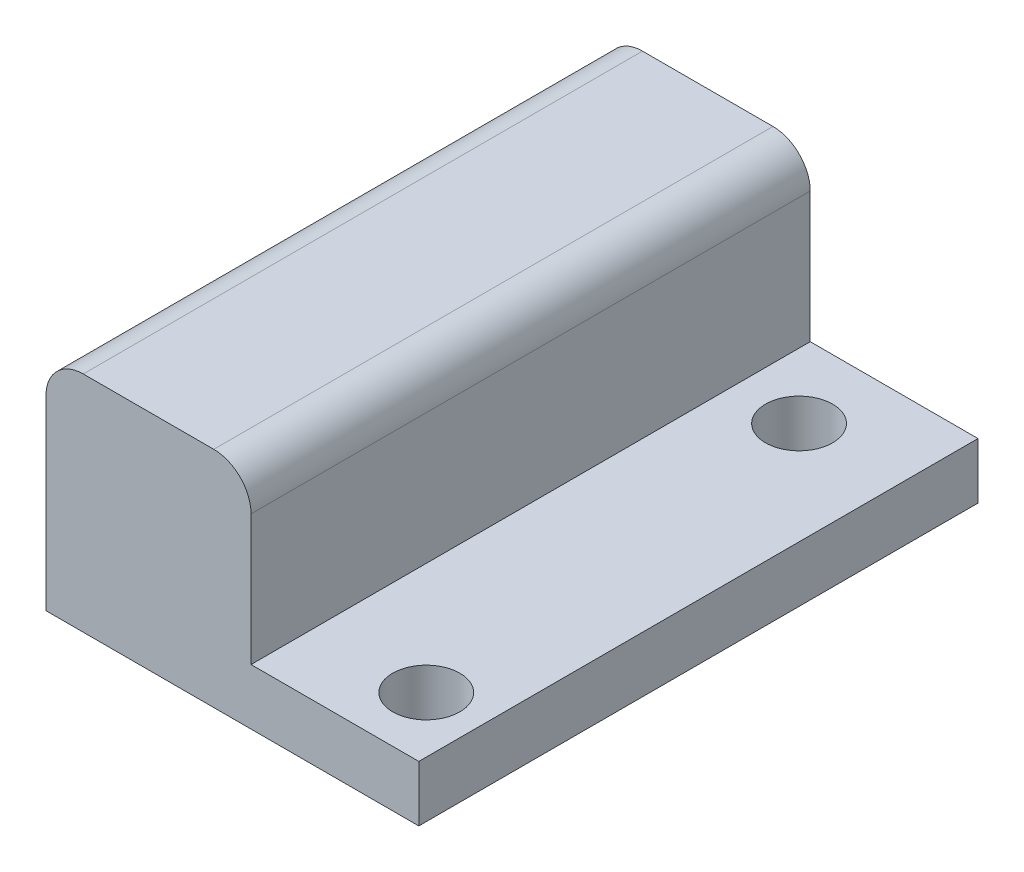
SolidWorks part; units mm, degrees
ref_plane "Front Plane" through (0, 0, 0) normal (0, 0, 1) x (1, 0, 0)
ref_plane "Top Plane" through (0, 0, 0) normal (0, 1, 0) x (1, 0, 0)
ref_plane "Right Plane" through (0, 0, 0) normal (1, 0, 0) x (0, 0, -1)
sketch "Sketch1" plane through (0, 0, 0) normal (0, 1, 0) x (1, 0, 0)
  line L1 (-19.812, 6.4835) -> (5.588, 6.4835)
  line L2 (-19.812, 6.4835) -> (-19.812, -31.6165)
  line L3 (-19.812, -31.6165) -> (5.588, -31.6165)
  line L4 (5.588, 6.4835) -> (5.588, -31.6165)
  circle A0 centre (-1.397, 1.2765) radius 2.286
  circle A1 centre (1.778, -27.2985) radius 2.286
  point P5 (0, 0)
  point P6 (-19.812, -12.5665)
  point P11 (0, 0)
  point P12 (0.508, -12.5665)
  point P13 (-1.9309, -28.9676)
  point P14 (1.7682, 1.088)
  point P15 (0, 0)
  point P16 (-2.1793, 1.2765)
  dimension "D1" = 28.575
  dimension "D2" = 4.572
  dimension "D3" = 3.81
  dimension "D4" = 3.175
  dimension "D5" = 38.1
  dimension "D6" = 25.4
  dimension "D7" = 4.318
extrude "Boss-Extrude1" add sketch "Sketch1" along normal blind 3.81
sketch "Sketch2" plane through (0, 3.81, 0) normal (0, 1, 0) x (1, 0, 0)
  line L0 (-19.812, 6.4835) -> (-19.812, -31.6165)
  line L1 (-19.812, -31.6165) -> (-5.842, -31.6165)
  line L2 (-19.812, -31.6165) -> (5.588, -31.6165) construction
  line L3 (-5.842, -31.6165) -> (-5.842, 6.4835)
  line L4 (5.588, 6.4835) -> (-19.812, 6.4835) construction
  line L5 (-5.842, 6.4835) -> (-8.382, 6.4835)
  line L6 (-8.382, 6.4835) -> (-8.382, -29.0765)
  line L7 (-8.382, -29.0765) -> (-17.272, -29.0765)
  line L8 (-17.272, -29.0765) -> (-17.272, 6.4835)
  line L9 (-17.272, 6.4835) -> (-19.812, 6.4835)
  dimension "D1" = 2.54
  dimension "D2" = 8.89
  dimension "D3" = 2.54
extrude "Boss-Extrude2" add sketch "Sketch2" along normal blind 8.89 contours L0 L1 L3 L5 L6 L7 L8 L9
sketch "Sketch3" plane through (0, 12.7, 0) normal (0, 1, 0) x (1, 0, 0)
  line L1 (-19.812, 6.4835) -> (-5.842, 6.4835)
  line L2 (-19.812, 6.4835) -> (-19.812, -31.6165)
  line L3 (-19.812, -31.6165) -> (-5.842, -31.6165)
  line L4 (-5.842, 6.4835) -> (-5.842, -31.6165)
extrude "Boss-Extrude3" add sketch "Sketch3" along normal blind 2.54
chamfer "Chamfer1" distance 1.27 angle 45 2 edges at (-8.382, 12.7, 11.2965) (-17.272, 12.7, 11.2965)
fillet "Fillet2" radius 2.54 2 edges at (-5.842, 15.24, 12.5665) (-19.812, 15.24, 12.5665)
